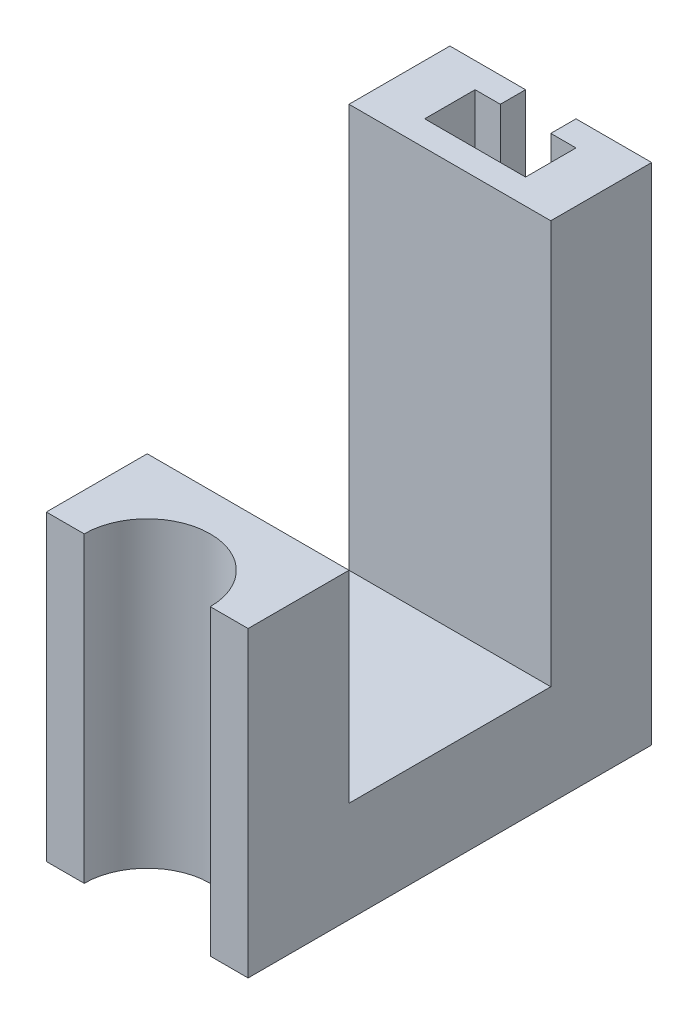
SolidWorks part; units mm, degrees
ref_plane "Front Plane" through (0, 0, 0) normal (0, 0, 1) x (1, 0, 0)
ref_plane "Top Plane" through (0, 0, 0) normal (0, 1, 0) x (1, 0, 0)
ref_plane "Right Plane" through (0, 0, 0) normal (1, 0, 0) x (0, 0, -1)
sketch "Sketch1" plane through (0, 0, 0) normal (0, 1, 0) x (1, 0, 0)
  line L1 (-21.3649, 33.484) -> (18.6351, 33.484)
  line L2 (-21.3649, 33.484) -> (-21.3649, -46.516)
  line L3 (-21.3649, -46.516) -> (18.6351, -46.516)
  line L4 (18.6351, 33.484) -> (18.6351, -46.516)
extrude "Boss-Extrude1" add sketch "Sketch1" along normal blind 100 contours L2 L1 L4 L3
sketch "Sketch3" plane through (18.6351, 0, 0) normal (1, 0, 0) x (0, 0, -1)
  line L0 (-26.516, 20) -> (13.484, 20)
  line L1 (13.484, 20) -> (13.484, 100)
  line L2 (33.484, 100) -> (-46.516, 100) construction
  line L3 (13.484, 100) -> (-26.516, 100)
  line L4 (-26.516, 100) -> (-26.516, 20)
  line L6 (33.484, 100) -> (33.484, 0) construction
  dimension "D1" = 20
extrude "Cut-Extrude1" cut sketch "Sketch3" against normal up to next contours L4 L0 L1 L3
sketch "Sketch5" plane through (18.6351, 0, 0) normal (1, 0, 0) x (0, 0, -1)
  line L0 (22, 0) -> (-22, 0) construction
  line L1 (-26.516, 0) -> (-46.516, 0)
  line L2 (-46.516, 100) -> (-46.516, 0) construction
  line L3 (-46.516, 0) -> (-46.516, 60)
  line L4 (-46.516, 60) -> (-26.516, 60)
  line L5 (-26.516, 100) -> (-26.516, 20) construction
  line L6 (-26.516, 60) -> (-26.516, 0)
  line L7 (-46.516, 60) -> (-46.516, 100)
  line L8 (-46.516, 100) -> (-26.516, 100)
  line L9 (-26.516, 100) -> (-26.516, 60)
  line M7 (-26.516, 20) -> (-26.516, 100)
  line M8 (-26.516, 100) -> (-46.516, 100)
  line M9 (-46.516, 100) -> (-46.516, 0)
extrude "Cut-Extrude2" cut sketch "Sketch5" against normal up to next contours L4 M9 M7 M8
sketch "Sketch6" plane through (0, 0, 0) normal (0, -1, 0) x (1, 0, 0)
  line L0 (-21.3649, 46.516) -> (18.6351, 46.516) construction
  circle A0 centre (-1.3649, 46.516) radius 12.5
extrude "Cut-Extrude3" cut sketch "Sketch6" against normal up to next contours A0
sketch "Sketch10" plane through (0, 0, 0) normal (0, -1, 0) x (1, 0, 0)
  line L0 (-11.3649, -18.484) -> (8.6351, -18.484)
  line L1 (-21.3649, -33.484) -> (18.6351, -33.484) construction
  line L2 (-11.3649, -18.484) -> (-11.3649, -28.484)
  line L3 (8.6351, -18.484) -> (8.6351, -28.484)
  line L4 (-11.3649, -28.484) -> (-6.3649, -28.484)
  line L5 (-6.3649, -28.484) -> (-6.3649, -33.484)
  line L6 (-6.3649, -33.484) -> (3.6351, -33.484)
  line L7 (3.6351, -33.484) -> (3.6351, -28.484)
  line L8 (3.6351, -28.484) -> (8.6351, -28.484)
  point P4 (-1.3649, -33.484)
  point P5 (-1.3649, -18.484)
extrude "Cut-Extrude5" cut sketch "Sketch10" against normal up to next contours L8 L3 L0 L2 L4 L5 L6 L7
